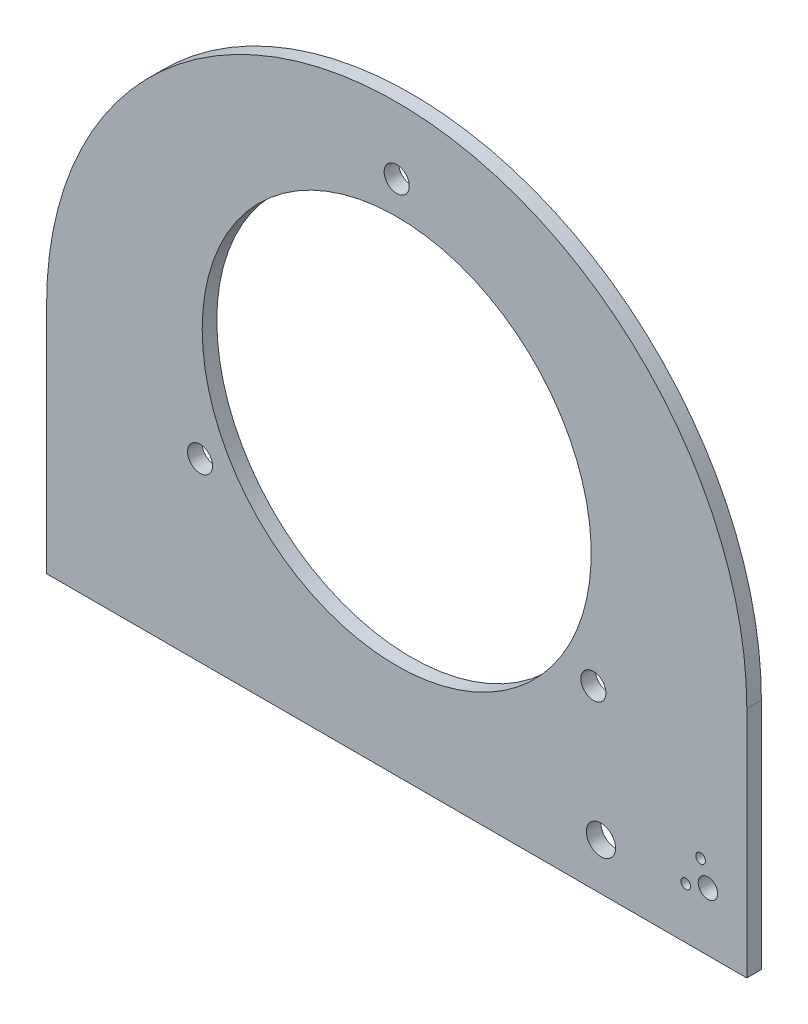
SolidWorks part; units mm, degrees
ref_plane "Front Plane" through (0, 0, 0) normal (0, 0, 1) x (1, 0, 0)
ref_plane "Top Plane" through (0, 0, 0) normal (0, 1, 0) x (1, 0, 0)
ref_plane "Right Plane" through (0, 0, 0) normal (1, 0, 0) x (0, 0, -1)
sketch "Sketch1" plane through (0, 0, 0) normal (0, 0, 1) x (1, 0, 0)
  line L0 (-228.6, -36.83) -> (-228.6, -189.23)
  line L1 (-228.6, -189.23) -> (228.6, -189.23)
  line L2 (-228.6, -189.23) -> (-228.6, 191.77) construction
  line L3 (-228.6, 191.77) -> (228.6, 191.77) construction
  line L4 (228.6, -189.23) -> (228.6, 191.77) construction
  line L5 (228.6, -36.83) -> (228.6, -189.23)
  line L6 (203.2, -151.13) -> (188.7233, -155.8925) construction
  line L7 (203.2, -151.13) -> (198.4375, -136.6533) construction
  circle A0 centre (0, 0) radius 127
  circle A1 centre (0, 148.2852) radius 8.1988
  arc A2 (228.6, -36.83) -> (-228.6, -36.83) centre (0, -36.83) ccw
  circle A3 centre (128.4188, -74.1426) radius 8.1988
  circle A4 centre (-128.4188, -74.1426) radius 8.1988
  circle A5 centre (203.2, -151.13) radius 6.35
  circle A6 centre (188.7233, -155.8925) radius 3.175
  circle A7 centre (198.4375, -136.6533) radius 3.175
  circle A8 centre (133.35, -158.75) radius 9.525
  point P19 (0, 0)
  dimension "D1" = 254
  dimension "D4" = 189.23
  dimension "D5" = 228.6
  dimension "D6" = 148.2852
  dimension "D8" = 12.7
  dimension "D9" = 38.1
  dimension "D10" = 25.4
  dimension "D11" = 15.24
  dimension "D12" = 6.35
  dimension "D13" = 33.3375
  dimension "D16" = 19.05
  dimension "D17" = 30.48
  dimension "D18" = 95.25
  dimension "D2" = 457.2
  dimension "D3" = 381
  dimension "D15" = 90
  dimension "D7" = 3
  dimension "D14" = 2
extrude "Boss-Extrude1" add sketch "Sketch1" along normal blind 9.525
